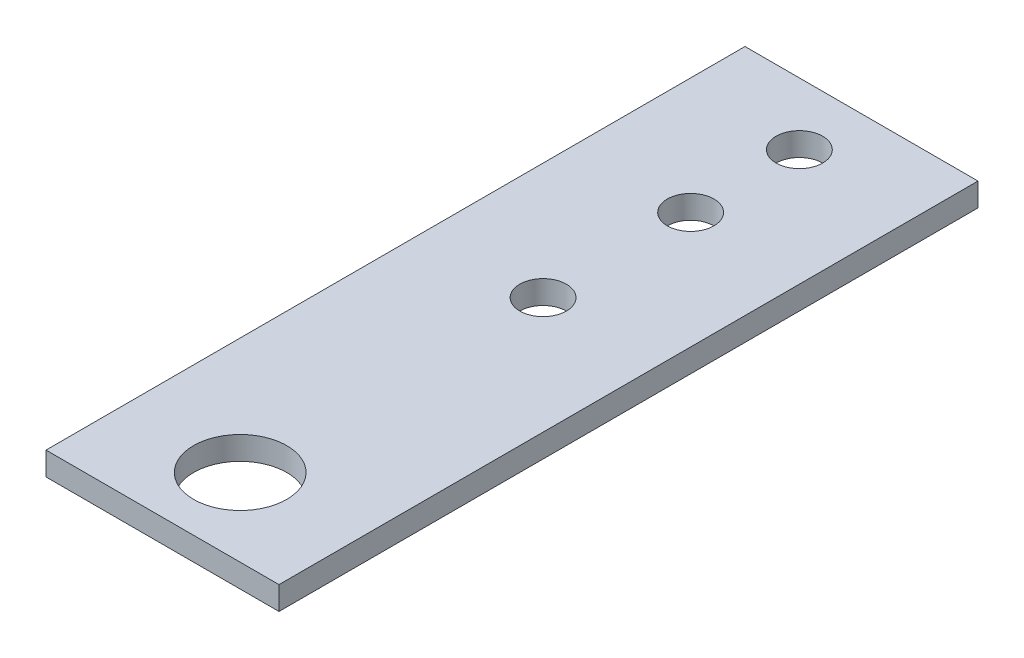
SolidWorks part; units mm, degrees
ref_plane "Plan de face" through (0, 0, 0) normal (0, 0, 1) x (1, 0, 0)
ref_plane "Plan de dessus" through (0, 0, 0) normal (0, 1, 0) x (1, 0, 0)
ref_plane "Plan de droite" through (0, 0, 0) normal (1, 0, 0) x (0, 0, -1)
sketch "Esquisse1" plane through (0, 0, 0) normal (0, 0, 1) x (1, 0, 0)
  line L1 (-8.9093, 3.1817) -> (6.0907, 3.1817)
  line L2 (-8.9093, 3.1817) -> (-8.9093, 1.6817)
  line L3 (-8.9093, 1.6817) -> (6.0907, 1.6817)
  line L4 (6.0907, 3.1817) -> (6.0907, 1.6817)
  dimension "D1" = 15
  dimension "D2" = 1.5
extrude "Extrusion1" add sketch "Esquisse1" along normal blind 45
sketch "Esquisse2" plane through (0, 3.1817, 0) normal (0, 1, 0) x (-1, 0, 0)
  line L0 (1.4093, 0) -> (1.4093, 30.5) construction
  line L1 (-6.0907, 0) -> (8.9093, 0) construction
  line L2 (-6.0907, 45) -> (8.9093, 45) construction
  line L4 (8.9093, 45) -> (-6.0907, 45) construction
  line L5 (1.4093, 30.5) -> (1.4093, 39.5) construction
  line L7 (1.4093, 39.5) -> (1.4093, 45) construction
  circle A0 centre (1.4093, 4) radius 1.5
  circle A1 centre (1.4093, 11) radius 1.5
  circle A2 centre (1.4093, 20.5) radius 1.5
  circle A3 centre (1.4093, 40) radius 3
  dimension "D2" = 7
  dimension "D4" = 5
  dimension "D1" = 20.5
  dimension "D3" = 4
extrude "Extrusion2" cut sketch "Esquisse2" against normal blind 50
